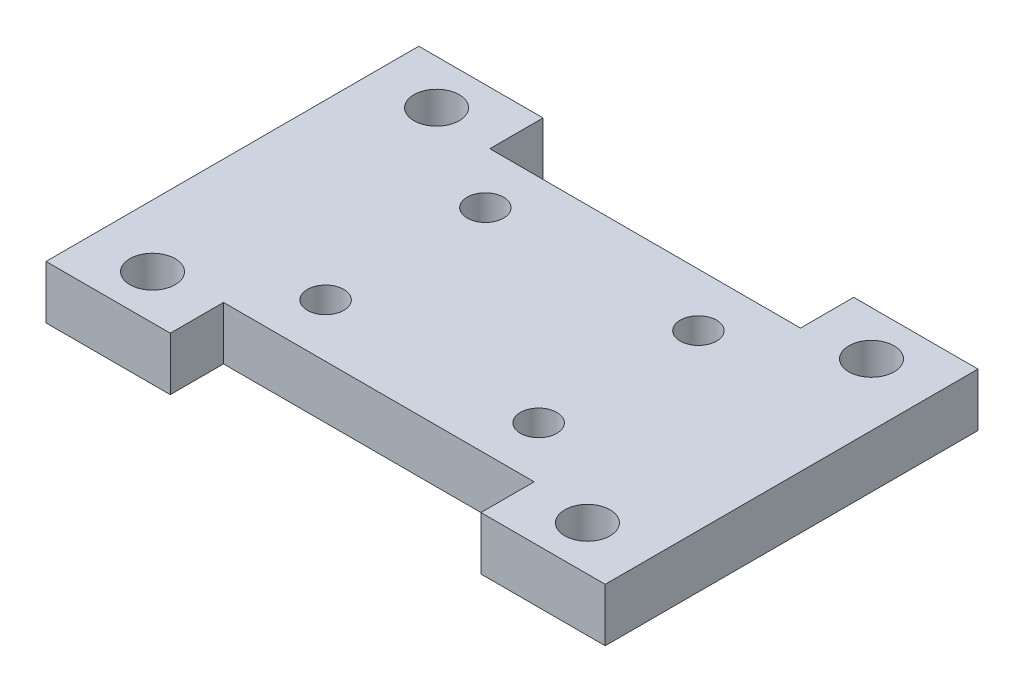
SolidWorks part; units mm, degrees
material "Alloy Steel"
ref_plane "Front Plane" through (0, 0, 0) normal (0, 0, 1) x (1, 0, 0)
ref_plane "Top Plane" through (0, 0, 0) normal (0, 1, 0) x (1, 0, 0)
ref_plane "Right Plane" through (0, 0, 0) normal (1, 0, 0) x (0, 0, -1)
sketch "Sketch1" plane through (0, 0, 0) normal (0, 1, 0) x (1, 0, 0)
  line L0 (0, 15) -> (0, -15) construction
  line L1 (-17.5, -15) -> (17.5, -15)
  line L3 (-17.5, 15) -> (17.5, 15)
  line L5 (-17.5, -15) -> (17.5, 15) construction
  line L6 (-17.5, 15) -> (17.5, -15) construction
  line L7 (-24.4406, 0) -> (25.4895, 0) construction
  line L8 (17.5, 15) -> (17.5, 21)
  line L9 (17.5, 21) -> (31.5, 21)
  line L10 (31.5, 21) -> (31.5, -21)
  line L11 (31.5, -21) -> (17.5, -21)
  line L12 (17.5, -21) -> (17.5, -15)
  line L13 (-17.5, -21) -> (-17.5, -15)
  line L14 (-31.5, -21) -> (-17.5, -21)
  line L15 (-31.5, 21) -> (-31.5, -21)
  line L16 (-17.5, 21) -> (-31.5, 21)
  line L17 (-17.5, 15) -> (-17.5, 21)
  circle A0 centre (-12, 9) radius 2.05
  circle A1 centre (12, 9) radius 2.05
  circle A2 centre (12, -9) radius 2.05
  circle A3 centre (-12, -9) radius 2.05
  circle A4 centre (24.5, 16) radius 2.55
  circle A5 centre (24.5, -16) radius 2.55
  circle A6 centre (-24.5, -16) radius 2.55
  circle A7 centre (-24.5, 16) radius 2.55
  point P0 (0, 0)
  point P20 (31.5, 0)
  point P25 (24.5, 21)
  dimension "D3" = 4.1
  dimension "D11" = 5.1
  dimension "D1" = 35
  dimension "D2" = 30
  dimension "D4" = 12
  dimension "D5" = 9
  dimension "D6" = 14
  dimension "D7" = 42
  dimension "D8" = 14
  dimension "D9" = 35
  dimension "D10" = 16
extrude "Boss-Extrude1" add sketch "Sketch1" along normal blind 6
ref_plane "Plane1" through (0, 0, 0) normal (-1, 0, 0) x (0, 0, 1)
